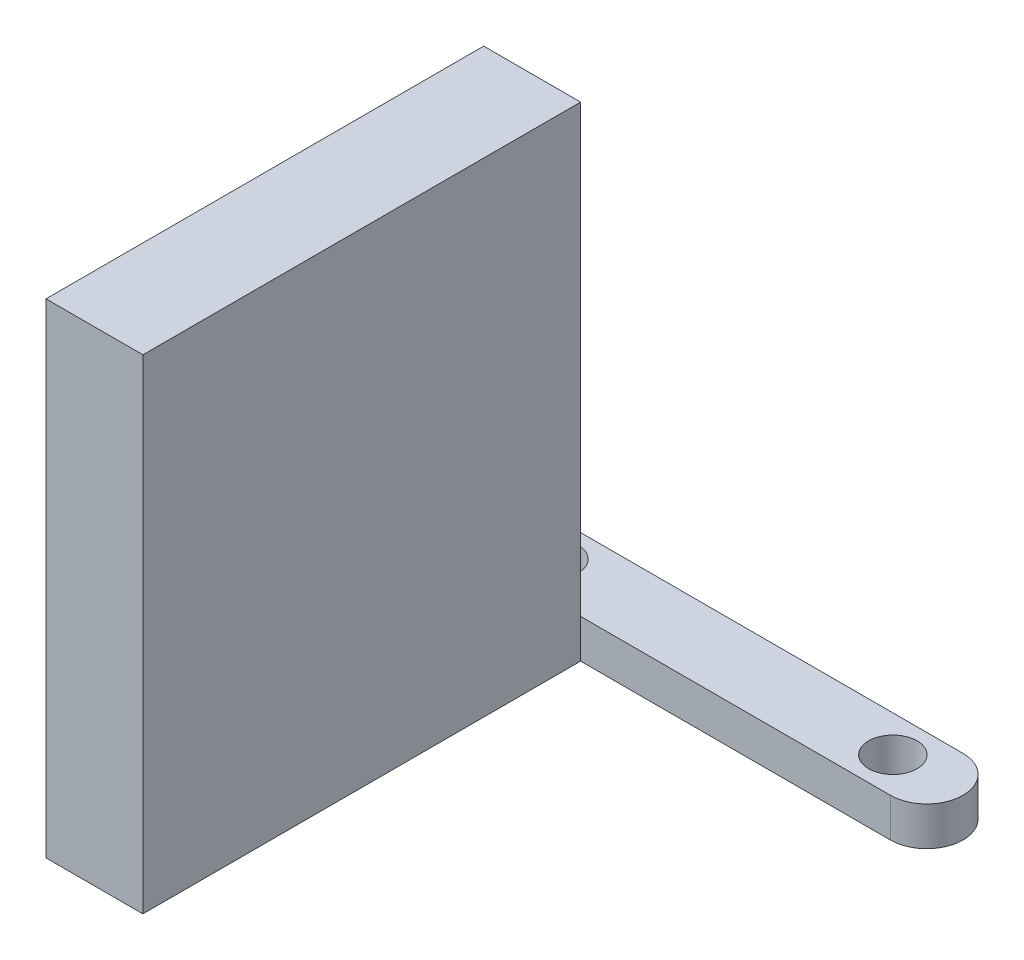
SolidWorks part; units mm, degrees
material "PLA"
ref_plane "Front Plane" through (0, 0, 0) normal (0, 0, 1) x (1, 0, 0)
ref_plane "Top Plane" through (0, 0, 0) normal (0, 1, 0) x (1, 0, 0)
ref_plane "Right Plane" through (0, 0, 0) normal (1, 0, 0) x (0, 0, -1)
sketch "Sketch1" plane through (0, 0, 0) normal (0, 1, 0) x (1, 0, 0)
  line L0 (-10.4941, -0.6865) -> (10.5059, -0.6865) construction
  line L1 (-10.4941, 1.1885) -> (10.5059, 1.1885)
  line L2 (-10.4941, -2.5615) -> (10.5059, -2.5615)
  line L3 (-10.4941, 1.1885) -> (-8.7441, -0.6865) construction
  line L4 (0.0059, -0.6865) -> (0.0059, 2.4383) construction
  arc A0 (-10.4941, 1.1885) -> (-10.4941, -2.5615) centre (-10.4941, -0.6865) ccw
  arc A1 (10.5059, -2.5615) -> (10.5059, 1.1885) centre (10.5059, -0.6865) ccw
  circle A2 centre (-8.7441, -0.6865) radius 1.25
  circle A3 centre (8.7559, -0.6865) radius 1.25
  point P2 (0.0059, -0.6865)
  dimension "D1" = 21
  dimension "D2" = 3.75
  dimension "D3" = 1.75
  dimension "D4" = 1.875
  dimension "D5" = 17.5
extrude "Boss-Extrude1" add sketch "Sketch1" along normal blind 2
sketch "Sketch2" plane through (0, 0, 0) normal (0, -1, 0) x (1, 0, 0)
  line L1 (-10.4941, 2.5615) -> (-5.4903, 2.5615)
  line L2 (-10.4941, 2.5615) -> (-10.4941, 25.1615)
  line L3 (-10.4941, 25.1615) -> (-5.4903, 25.1615)
  line L4 (-5.4903, 2.5615) -> (-5.4903, 25.1615)
  dimension "D1" = 22.6
  dimension "D2" = 5.0038
extrude "Boss-Extrude2" add sketch "Sketch2" against normal blind 25
